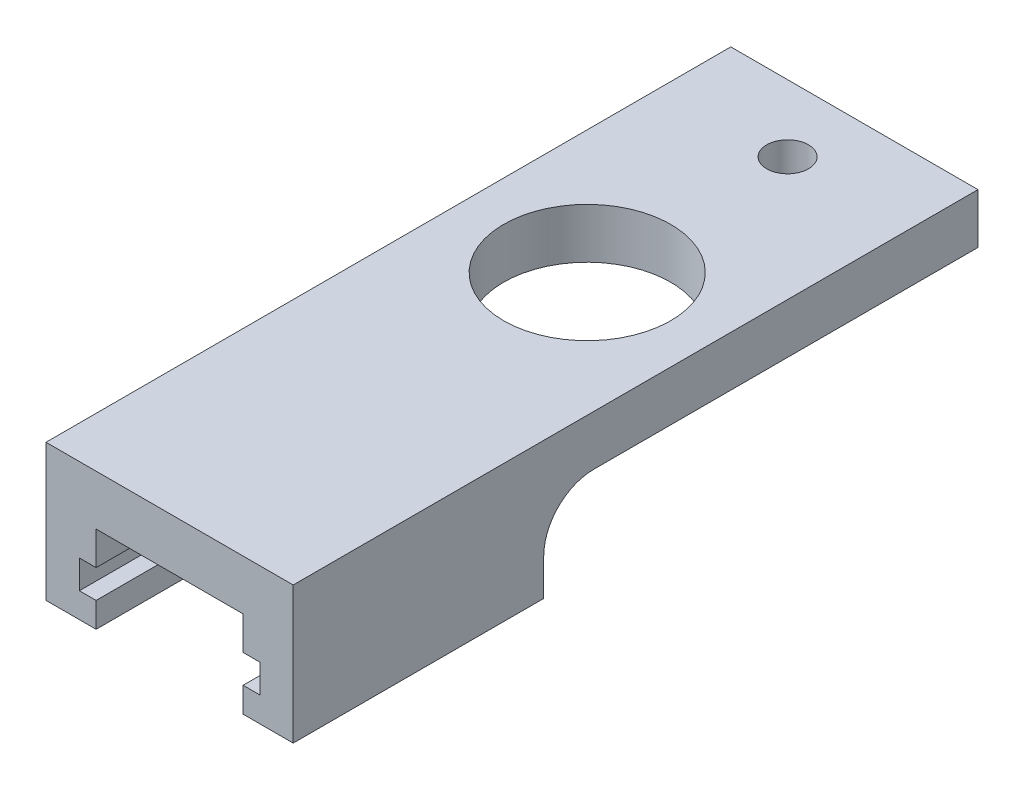
SolidWorks part; units mm, degrees
ref_plane "Front Plane" through (0, 0, 0) normal (0, 0, 1) x (1, 0, 0)
ref_plane "Top Plane" through (0, 0, 0) normal (0, 1, 0) x (1, 0, 0)
ref_plane "Right Plane" through (0, 0, 0) normal (1, 0, 0) x (0, 0, -1)
sketch "Sketch1" plane through (0, 0, 0) normal (0, 1, 0) x (1, 0, 0)
  line L1 (-7.4, -7.5) -> (7.4, -7.5)
  line L2 (-7.4, -7.5) -> (-7.4, 7.5)
  line L3 (-7.4, 7.5) -> (7.4, 7.5)
  line L4 (7.4, -7.5) -> (7.4, 7.5)
  line L5 (-7.4, -7.5) -> (7.4, 7.5) construction
  line L6 (-7.4, 7.5) -> (7.4, -7.5) construction
  point P0 (0, 0)
  dimension "D1" = 15
  dimension "D2" = 14.8
extrude "Boss-Extrude1" add sketch "Sketch1" along normal blind 8.2
sketch "Sketch3" plane through (0, 0, 7.5) normal (0, 0, 1) x (1, 0, 0)
  line L0 (-7.4, 0) -> (7.4, 0) construction
  line L1 (-4.4, 0) -> (4.4, 0)
  line L2 (-4.4, 0) -> (-4.4, 5.2)
  line L3 (-4.4, 5.2) -> (4.4, 5.2)
  line L4 (4.4, 0) -> (4.4, 5.2)
  line L5 (-7.4, 8.2) -> (7.4, 8.2) construction
  line L6 (7.4, 8.2) -> (7.4, 0) construction
  line L7 (-7.4, 8.2) -> (-7.4, 0) construction
  dimension "D1" = 3
  dimension "D2" = 3
  dimension "D3" = 3
extrude "Cut-Extrude1" cut sketch "Sketch3" against normal blind 12
sketch "Sketch5" plane through (0, 0, 7.5) normal (0, 0, 1) x (1, 0, 0)
  line L1 (-5.4, 1.5) -> (5.4, 1.5)
  line L2 (-5.4, 1.5) -> (-5.4, 3.2)
  line L3 (-5.4, 3.2) -> (5.4, 3.2)
  line L4 (5.4, 1.5) -> (5.4, 3.2)
  line L5 (4.4, 5.2) -> (-4.4, 5.2) construction
  line L6 (7.4, 8.2) -> (7.4, 0) construction
  line L7 (-7.4, 8.2) -> (-7.4, 0) construction
  dimension "D1" = 2
  dimension "D2" = 2
  dimension "D3" = 2
  dimension "D4" = 1.7
extrude "Cut-Extrude2" cut sketch "Sketch5" against normal blind 12
sketch "Sketch6" plane through (0, 0, -7.5) normal (0, 0, -1) x (-1, 0, 0)
  line L0 (-7.4, 8.2) -> (-7.4, 0) construction
  line L1 (-7.4, 5.2) -> (7.4, 5.2)
  line L2 (-7.4, 5.2) -> (-7.4, 8.2)
  line L3 (-7.4, 8.2) -> (7.4, 8.2)
  line L4 (7.4, 5.2) -> (7.4, 8.2)
  dimension "D1" = 3
extrude "Boss-Extrude2" add sketch "Sketch6" along normal blind 26
sketch "Sketch7" plane through (0, 8.2, 0) normal (0, 1, 0) x (1, 0, 0)
  line L0 (-7.4, -7.5) -> (7.4, -7.5) construction
  circle A0 centre (0, 17.5) radius 5
  dimension "D1" = 10
  dimension "D2" = 25
extrude "Cut-Extrude3" cut sketch "Sketch7" against normal through all
sketch "Sketch8" plane through (0, 8.2, 0) normal (0, 1, 0) x (1, 0, 0)
  line L0 (-7.4, 33.5) -> (7.4, 33.5) construction
  point P0 (0, 29.5)
  dimension "D1" = 4
hole_wizard "M3x0.5 Tapped Hole1" positions "Sketch8" profile "Sketch9" tap size "M3x0.5" standard "ANSI Metric"
sketch "Sketch9" plane through (0, 8.2, -29.5) normal (1, 0, 0) x (0, 0, 1)
  line L0 (0, 0) -> (0, 8.2511)
  line L1 (0, 8.2511) -> (1.25, 7.5)
  line L2 (1.25, 7.5) -> (1.25, 0)
  line L5 (1.25, 0) -> (0, 0)
  line L10 (0, 8.2511) -> (-1.25, 7.5) construction
  line L11 (0, -6.35) -> (0, 107.95) construction
  dimension "Tap Drill Dia." = 2.5
  dimension "Tap Drill Depth" = 7.5
  dimension "Drill Angle" = 118
cosmetic thread "Hole Thread1" parameters "D1"=6, "D2"=3
fillet "Fillet1" radius 3 1 edges at (0, 5.2, -7.5)
